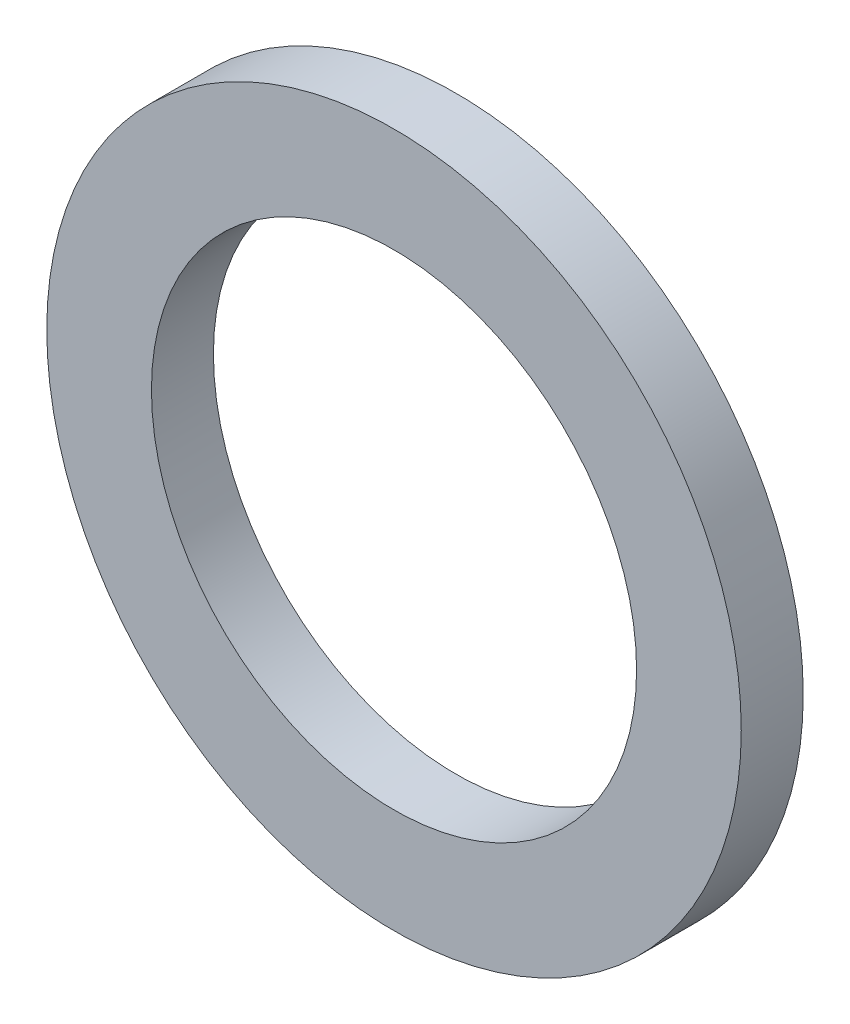
SolidWorks part; units mm, degrees
material "NEOPRENE"
ref_plane "Front Plane" through (0, 0, 0) normal (0, 0, 1) x (1, 0, 0)
ref_plane "Top Plane" through (0, 0, 0) normal (0, 1, 0) x (1, 0, 0)
ref_plane "Right Plane" through (0, 0, 0) normal (1, 0, 0) x (0, 0, -1)
sketch "Sketch1" plane through (0, 0, 0) normal (0, 0, 1) x (1, 0, 0)
  circle A0 centre (0, 0) radius 26.543
  circle A1 centre (0, 0) radius 18.542
extrude "Boss-Extrude1" add sketch "Sketch1" along normal blind 4.7371 contours A1 | A0
